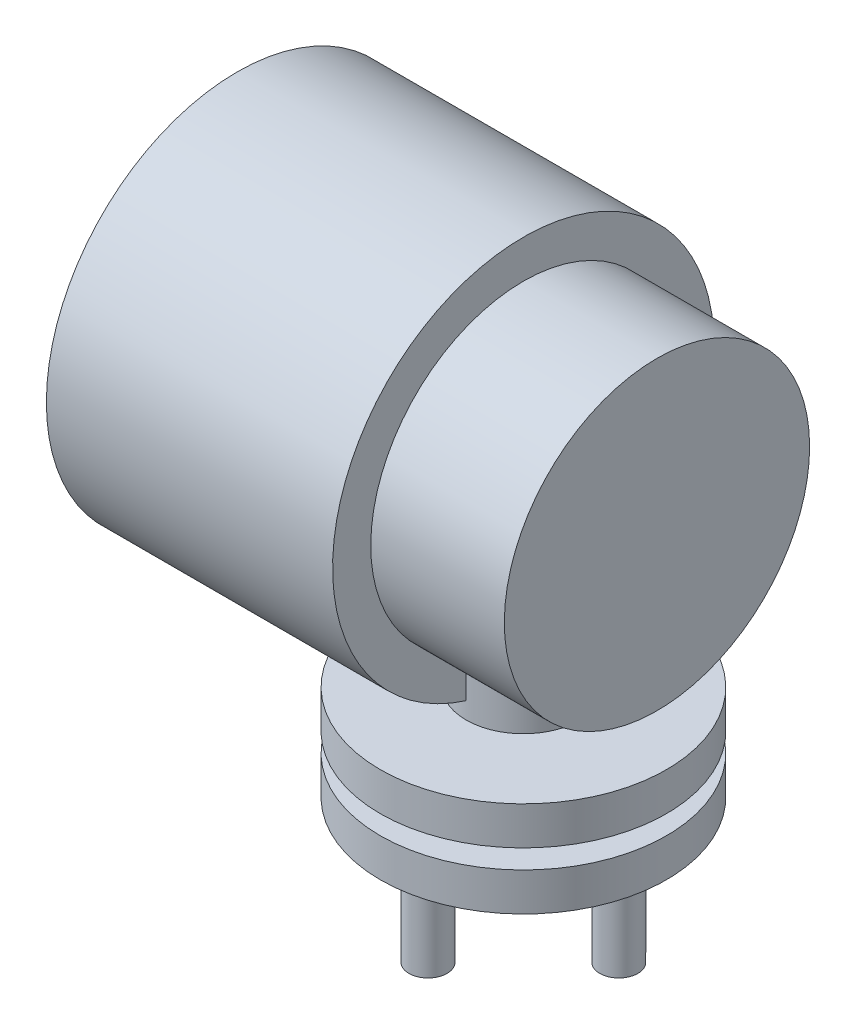
SolidWorks part; units mm, degrees
ref_plane "Front Plane" through (0, 0, 0) normal (0, 0, 1) x (1, 0, 0)
ref_plane "Top Plane" through (0, 0, 0) normal (0, 1, 0) x (1, 0, 0)
ref_plane "Right Plane" through (0, 0, 0) normal (1, 0, 0) x (0, 0, -1)
sketch "Sketch1" plane through (0, 0, 0) normal (0, 1, 0) x (1, 0, 0)
  circle A0 centre (0, 0) radius 75
extrude "Boss-Extrude1" add sketch "Sketch1" along normal blind 20
sketch "Sketch2" plane through (0, 20, 0) normal (0, 1, 0) x (1, 0, 0)
  circle A0 centre (0, 0) radius 60
extrude "Boss-Extrude2" add sketch "Sketch2" along normal blind 10
sketch "Sketch3" plane through (0, 30, 0) normal (0, 1, 0) x (1, 0, 0)
  circle A0 centre (0, 0) radius 75
extrude "Boss-Extrude3" add sketch "Sketch3" along normal blind 20
sketch "Sketch4" plane through (0, 50, 0) normal (0, 1, 0) x (1, 0, 0)
  circle A0 centre (0, 0) radius 30
extrude "Boss-Extrude4" add sketch "Sketch4" along normal blind 100
sketch "Sketch5" plane through (0, 0, 0) normal (1, 0, 0) x (0, 0, -1)
  line L0 (0, 0) -> (0, 154.2018) construction
  circle A0 centre (0, 154.2018) radius 100
extrude "Boss-Extrude5" add sketch "Sketch5" against normal blind 150
sketch "Sketch6" plane through (0, 0, 0) normal (1, 0, 0) x (0, 0, -1)
  circle A0 centre (0, 154.2018) radius 80
extrude "Boss-Extrude6" add sketch "Sketch6" along normal blind 70
sketch "Sketch7" plane through (0, 0, 0) normal (0, -1, 0) x (-1, 0, 0)
  circle A2 centre (0, 50) radius 10
  circle A3 centre (-50, 0) radius 10
  circle A4 centre (0, -50) radius 10
  circle A5 centre (50, 0) radius 10
extrude "Boss-Extrude7" add sketch "Sketch7" along normal blind 40
sketch "Sketch13" plane through (0, 0, 0) normal (0, -1, 0) x (-1, 0, 0)
  circle A0 centre (0, 0) radius 25
extrude "Cut-Extrude1" cut sketch "Sketch13" against normal blind 120
sketch "Sketch14" plane through (0, -40, 0) normal (0, -1, 0) x (-1, 0, 0)
  circle A1 centre (0, 50) radius 10
  circle A2 centre (50, 0) radius 10
  circle A3 centre (0, -50) radius 10
  circle A4 centre (-50, 0) radius 10
extrude "Boss-Extrude8" add sketch "Sketch14" along normal blind 10
